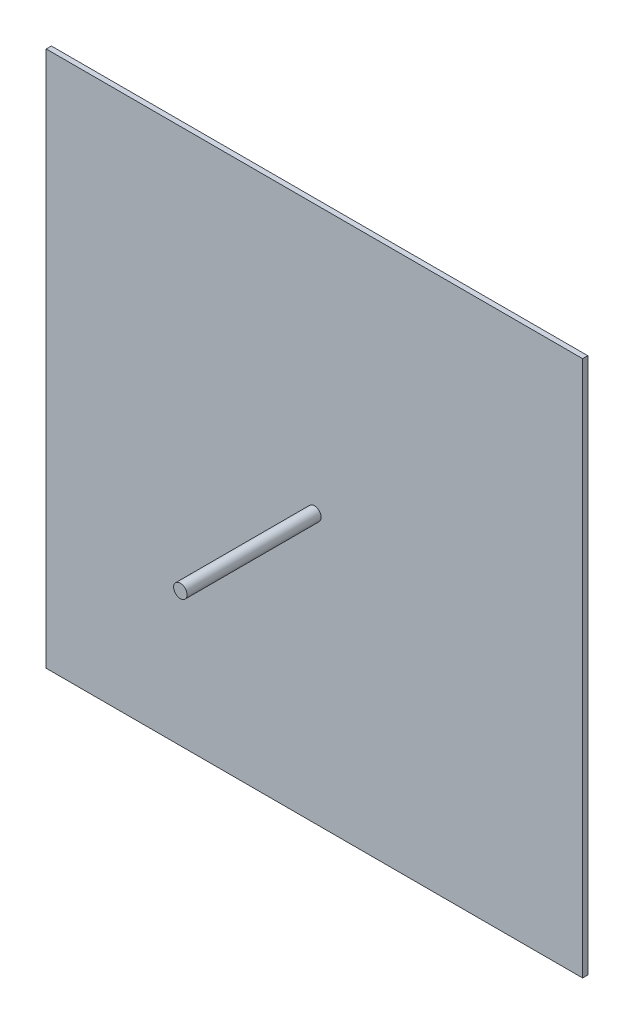
SolidWorks part; units mm, degrees
ref_plane "Front Plane" through (0, 0, 0) normal (0, 0, 1) x (1, 0, 0)
ref_plane "Top Plane" through (0, 0, 0) normal (0, 1, 0) x (1, 0, 0)
ref_plane "Right Plane" through (0, 0, 0) normal (1, 0, 0) x (0, 0, -1)
sketch "Sketch3" plane through (0, 0, 0) normal (0, 0, 1) x (1, 0, 0)
  line L1 (-50.8, -50.8) -> (50.8, -50.8)
  line L2 (-50.8, -50.8) -> (-50.8, 50.8)
  line L3 (-50.8, 50.8) -> (50.8, 50.8)
  line L4 (50.8, -50.8) -> (50.8, 50.8)
  line L5 (-50.8, -50.8) -> (50.8, 50.8) construction
  line L6 (-50.8, 50.8) -> (50.8, -50.8) construction
  point P0 (0, 0)
  dimension "D1" = 101.6
  dimension "D2" = 101.6
extrude "Boss-Extrude2" add sketch "Sketch3" along normal blind 0.9779
sketch "Sketch4" plane through (0, 0, 0.9779) normal (0, 0, 1) x (1, 0, 0)
  circle A0 centre (0, 0) radius 1.27
  dimension "D1" = 2.54
extrude "Boss-Extrude3" add sketch "Sketch4" along normal blind 25.4
